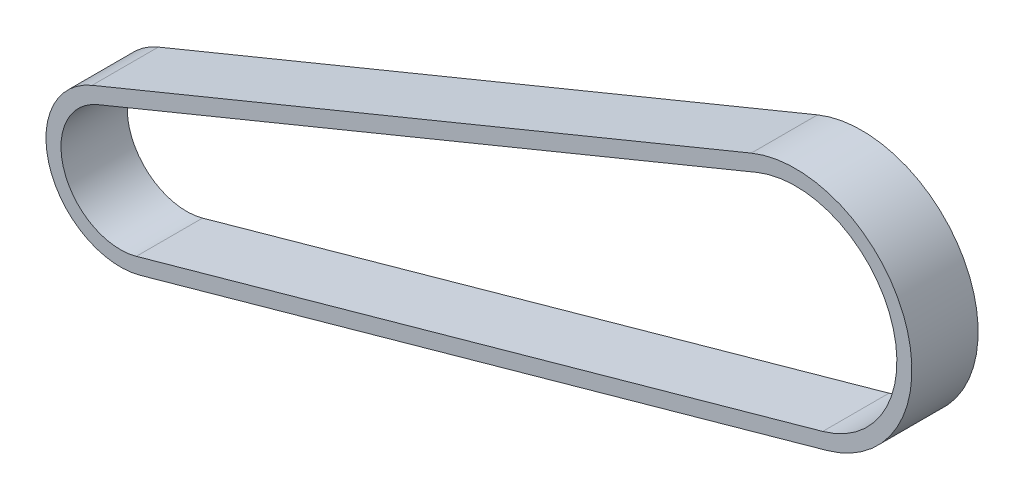
SolidWorks part; units mm, degrees
material "BUTYL"
ref_plane "Front Plane" through (0, 0, 0) normal (0, 0, 1) x (1, 0, 0)
ref_plane "Top Plane" through (0, 0, 0) normal (0, 1, 0) x (1, 0, 0)
ref_plane "Right Plane" through (0, 0, 0) normal (1, 0, 0) x (0, 0, -1)
sketch "Sketch1"
sketch_block_instance "Block1-1"
sketch_block "Block1"
sketch "Sketch2" plane through (0, 0, 0) normal (0, 0, 1) x (1, 0, 0)
  line L0 (-63.194, -16.0428) -> (-3.4897, 8.4919)
  line L1 (-59.7043, -26.1962) -> (2.4682, -8.843)
  line L2 (-59.3387, -27.5061) -> (2.8338, -10.1529)
  line L3 (-63.7109, -14.7849) -> (-4.0066, 9.7499)
  arc A0 (-63.194, -16.0428) -> (-59.7043, -26.1962) centre (-61.15, -21.0167) ccw
  arc A1 (2.4682, -8.843) -> (-3.4897, 8.4919) centre (0, 0) ccw
  circle A2 centre (0, 0) radius 9.181 construction
  circle A3 centre (-61.15, -21.0167) radius 5.3775 construction
  arc A4 (-63.7109, -14.7849) -> (-59.3387, -27.5061) centre (-61.15, -21.0167) ccw
  arc A5 (2.8338, -10.1529) -> (-4.0066, 9.7499) centre (0, 0) ccw
  dimension "D1" = 1.36
extrude "Boss-Extrude1" add sketch "Sketch2" along normal mid plane 6
